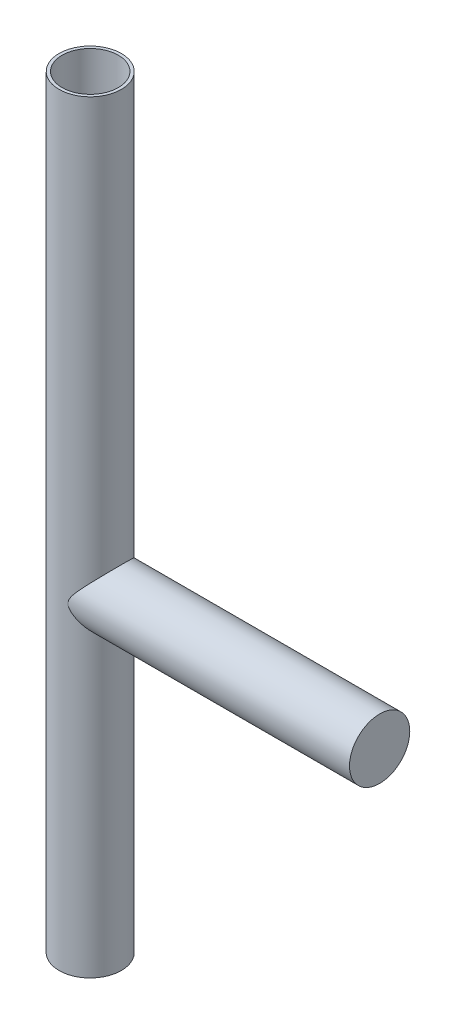
SolidWorks part; units mm, degrees
ref_plane "Front Plane" through (0, 0, 0) normal (0, 0, 1) x (1, 0, 0)
ref_plane "Top Plane" through (0, 0, 0) normal (0, 1, 0) x (1, 0, 0)
ref_plane "Right Plane" through (0, 0, 0) normal (1, 0, 0) x (0, 0, -1)
sketch "Sketch1" plane through (0, 0, 0) normal (0, 1, 0) x (1, 0, 0)
  circle A0 centre (0, 0) radius 7.75
  circle A1 centre (0, 0) radius 7
  dimension "D1" = 15.5
  dimension "D2" = 14
extrude "Boss-Extrude1" add sketch "Sketch1" along normal blind 160 and the other way blind 5
sketch "Sketch5" plane through (0, 0, 0) normal (1, 0, 0) x (0, 0, -1)
  circle A0 centre (0, 75) radius 7.5
  dimension "D1" = 15
extrude "Boss-Extrude3" add sketch "Sketch5" along normal blind 72.0622
sketch "Sketch7" plane through (0, 160, 0) normal (0, 1, 0) x (1, 0, 0)
  circle A0 centre (0, 0) radius 7
  circle A1 centre (0, 0) radius 7.75
extrude "Boss-Extrude5" add sketch "Sketch7" along normal blind 25
